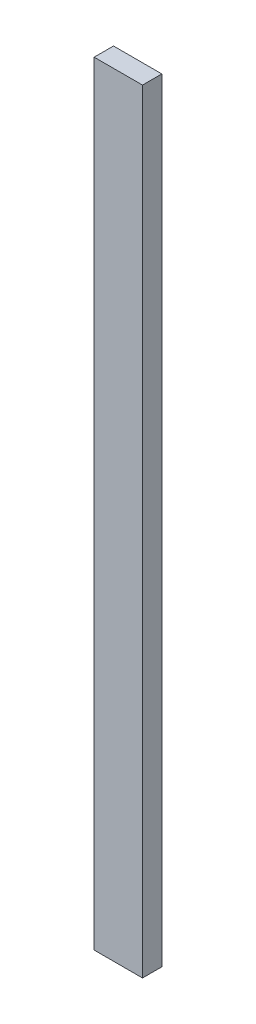
SolidWorks part; units mm, degrees
ref_plane "前视基准面" through (0, 0, 0) normal (0, 0, 1) x (1, 0, 0)
ref_plane "上视基准面" through (0, 0, 0) normal (0, 1, 0) x (1, 0, 0)
ref_plane "右视基准面" through (0, 0, 0) normal (1, 0, 0) x (0, 0, -1)
sketch "草图1" plane through (0, 0, 0) normal (0, 0, 1) x (1, 0, 0)
  line L1 (-125, 2000) -> (125, 2000)
  line L2 (-125, 2000) -> (-125, -2000)
  line L3 (-125, -2000) -> (125, -2000)
  line L4 (125, 2000) -> (125, -2000)
  line L5 (0, -2000) -> (0, 2000) construction
  line L6 (-125, 0) -> (125, 0) construction
  point P0 (0, 0)
  dimension "D1" = 4000
  dimension "D2" = 250
extrude "凸台-拉伸1" add sketch "草图1" along normal blind 100
